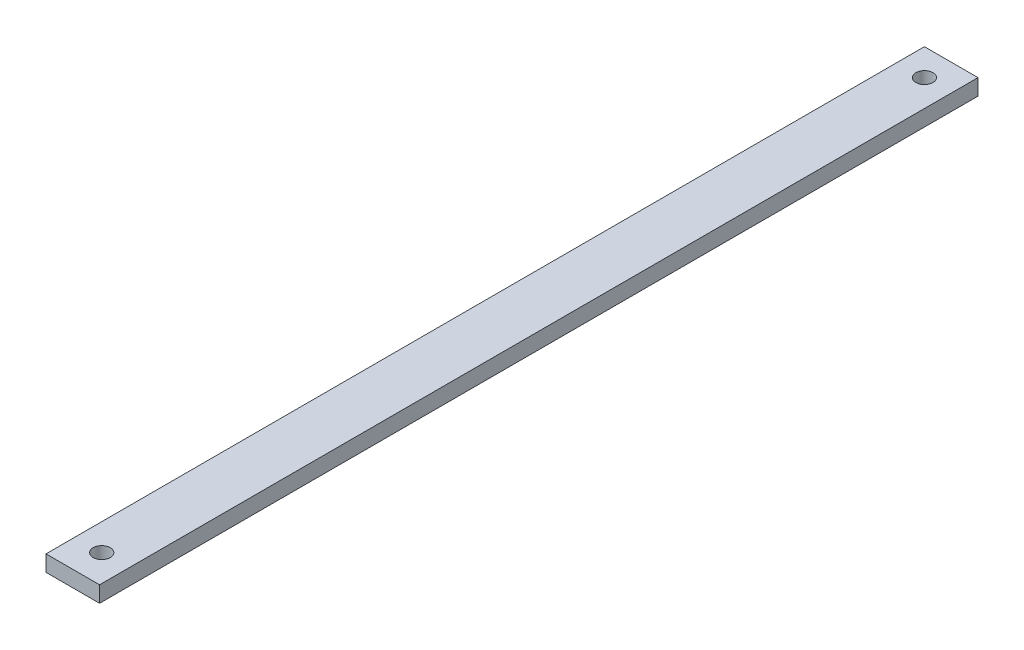
SolidWorks part; units mm, degrees
ref_plane "Front Plane" through (0, 0, 0) normal (0, 0, 1) x (1, 0, 0)
ref_plane "Top Plane" through (0, 0, 0) normal (0, 1, 0) x (1, 0, 0)
ref_plane "Right Plane" through (0, 0, 0) normal (1, 0, 0) x (0, 0, -1)
sketch "Sketch1" plane through (0, 0, 0) normal (0, 1, 0) x (1, 0, 0)
  line L1 (0, 0) -> (10, 0)
  line L2 (0, 0) -> (0, 164)
  line L3 (0, 164) -> (10, 164)
  line L4 (10, 0) -> (10, 164)
  dimension "D1" = 10
  dimension "D2" = 164
extrude "Boss-Extrude1" add sketch "Sketch1" along normal blind 3
sketch "Sketch2" plane through (0, 3, 0) normal (0, 1, 0) x (1, 0, 0)
  line L0 (10, 164) -> (0, 164) construction
  line L1 (10, 0) -> (10, 164) construction
  circle A0 centre (5, 159) radius 1.6
  circle A1 centre (5, 5.4) radius 1.6
  dimension "D1" = 3.2
  dimension "D4" = 3.2
  dimension "D2" = 5
  dimension "D3" = 5
  dimension "D5" = 153.6
  dimension "D6" = 5
extrude "Cut-Extrude1" cut sketch "Sketch2" against normal blind 10
